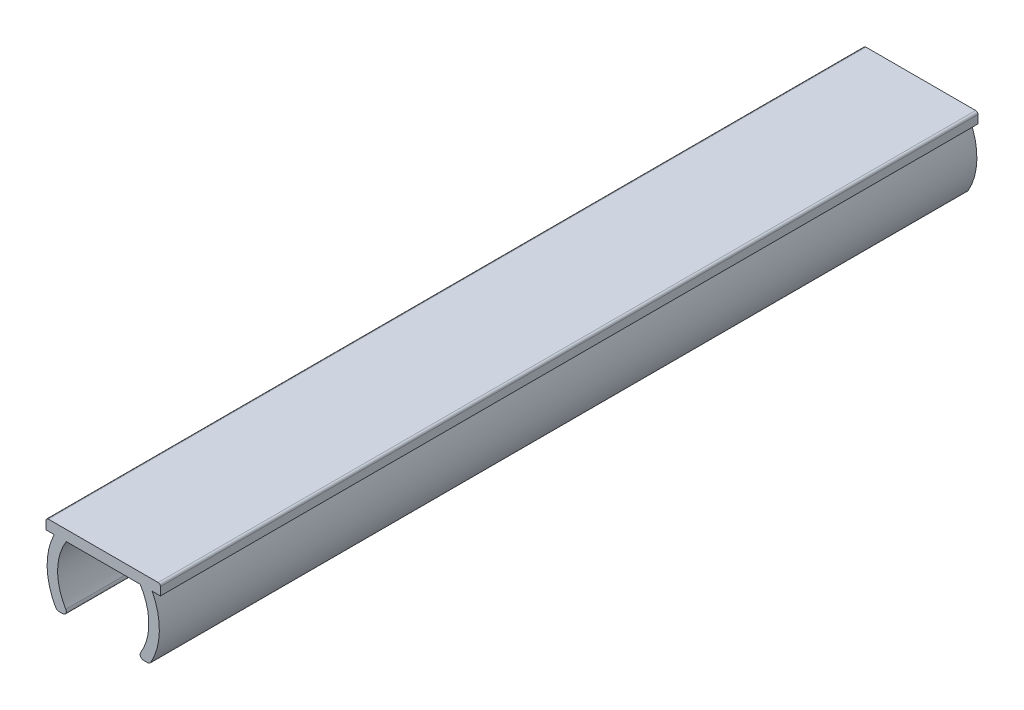
SolidWorks part; units mm, degrees
ref_plane "前视基准面" through (0, 0, 0) normal (0, 0, 1) x (1, 0, 0)
ref_plane "上视基准面" through (0, 0, 0) normal (0, 1, 0) x (1, 0, 0)
ref_plane "右视基准面" through (0, 0, 0) normal (1, 0, 0) x (0, 0, -1)
sketch "草图1" plane through (0, 0, 0) normal (0, 0, 1) x (1, 0, 0)
  line B0 (0.2, 0.9) -> (9.6, 0.9)
  line B1 (0, 0) -> (0, 0.7)
  line B2 (9.8, 0.7) -> (9.8, 0)
  line B3 (0, 0) -> (0.7041, 0)
  line B4 (1.7382, 0) -> (8.0618, 0)
  line B5 (9.0959, 0) -> (9.8, 0)
  line B6 (8.3583, -5.5) -> (8.7066, -5.5)
  line B7 (1.4417, -5.5) -> (1.0934, -5.5)
  arc B8 (0.2, 0.9) -> (0, 0.7) centre (0.2, 0.7) ccw
  arc B9 (9.8, 0.7) -> (9.6, 0.9) centre (9.6, 0.7) ccw
  arc B10 (8.9675, -5.348) -> (9.0959, 0) centre (4.043, -2.5542) ccw
  arc B11 (8.1026, -5.0432) -> (8.0618, 0) centre (4.043, -2.5542) ccw
  arc B12 (8.1026, -5.0432) -> (8.3583, -5.5) centre (8.3583, -5.2) ccw
  arc B13 (8.7066, -5.5) -> (8.9675, -5.348) centre (8.7066, -5.2) ccw
  arc B14 (0.7041, 0) -> (0.8325, -5.348) centre (5.757, -2.5542) ccw
  arc B15 (1.7382, 0) -> (1.6974, -5.0432) centre (5.757, -2.5542) ccw
  arc B16 (1.4417, -5.5) -> (1.6974, -5.0432) centre (1.4417, -5.2) ccw
  arc B17 (0.8325, -5.348) -> (1.0934, -5.5) centre (1.0934, -5.2) ccw
sketch_block_instance "A$C4D4147AE-1"
sketch_block "A$C4D4147AE"
extrude "凸台-拉伸1" add sketch "草图1" along normal blind 70
